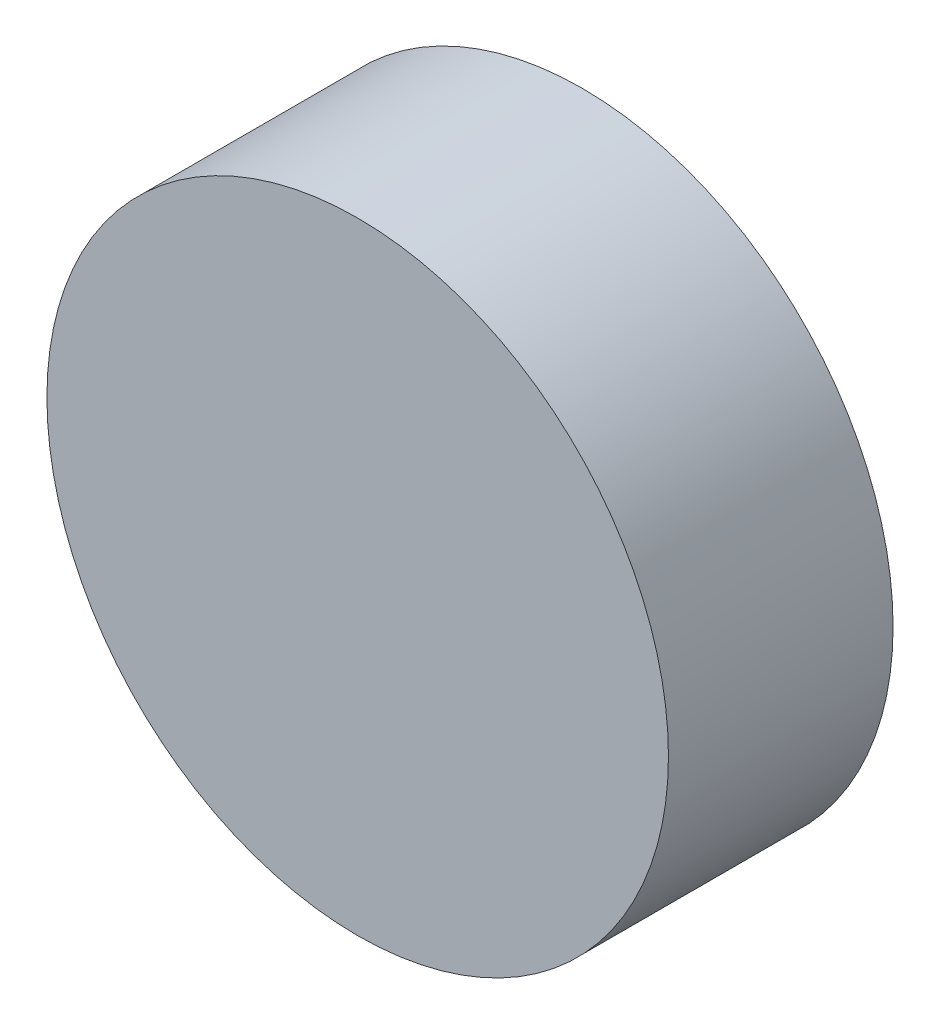
SolidWorks part; units mm, degrees
ref_plane "前视基准面" through (0, 0, 0) normal (0, 0, 1) x (1, 0, 0)
ref_plane "上视基准面" through (0, 0, 0) normal (0, 1, 0) x (1, 0, 0)
ref_plane "右视基准面" through (0, 0, 0) normal (1, 0, 0) x (0, 0, -1)
other "Configuration Table"
sketch "草图1" plane through (0, 0, 0) normal (0, 0, 1) x (1, 0, 0)
  circle A0 centre (0, 0) radius 25
extrude "Measured_knob_D50_H18p07" add sketch "草图1" along normal blind 18.07
